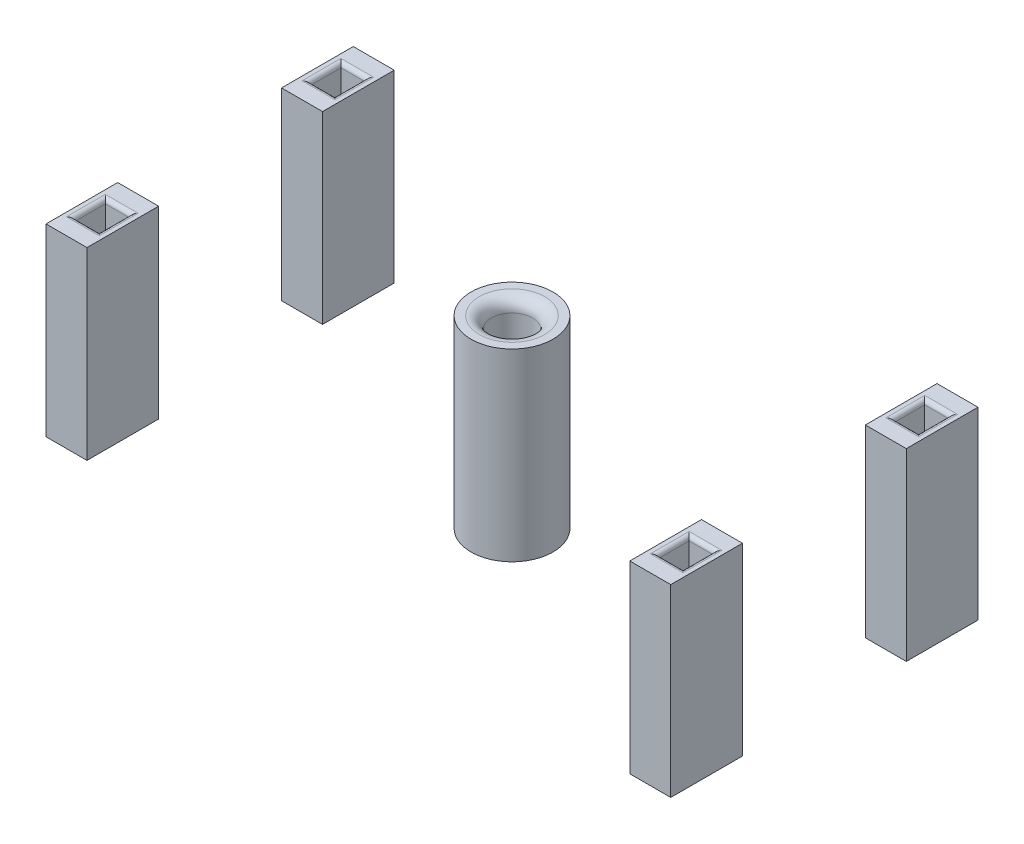
SolidWorks part; units mm, degrees
ref_plane "Front Plane" through (0, 0, 0) normal (0, 0, 1) x (1, 0, 0)
ref_plane "Top Plane" through (0, 0, 0) normal (0, 1, 0) x (1, 0, 0)
ref_plane "Right Plane" through (0, 0, 0) normal (1, 0, 0) x (0, 0, -1)
sketch "Sketch1" plane through (0, 0, 0) normal (0, 1, 0) x (1, 0, 0)
  line L0 (-55, 0) -> (55, 0) construction
  line L1 (-82.5, 43) -> (82.5, 43)
  line L2 (-82.5, 43) -> (-82.5, -43)
  line L3 (-82.5, -43) -> (82.5, -43)
  line L4 (82.5, 43) -> (82.5, -43)
  line L5 (-82.5, 43) -> (82.5, -43) construction
  line L6 (-82.5, -43) -> (82.5, 43) construction
  line L7 (-76.25, 37.5) -> (-66.25, 37.5)
  line L8 (-76.25, 37.5) -> (-76.25, -37.5)
  line L9 (-76.25, -37.5) -> (-66.25, -37.5)
  line L10 (-66.25, 37.5) -> (-66.25, -37.5)
  line L11 (-76.25, 37.5) -> (-66.25, -37.5) construction
  line L12 (-76.25, -37.5) -> (-66.25, 37.5) construction
  line L13 (-76.25, 20) -> (-66.25, 20)
  line L14 (-76.25, 20) -> (-76.25, -20)
  line L15 (-76.25, -20) -> (-66.25, -20)
  line L16 (-66.25, 20) -> (-66.25, -20)
  line L17 (-76.25, 20) -> (-66.25, -20) construction
  line L18 (-76.25, -20) -> (-66.25, 20) construction
  line L19 (-74.25, 32.5) -> (-68.25, 32.5)
  line L20 (-74.25, 32.5) -> (-74.25, 25)
  line L21 (-74.25, 25) -> (-68.25, 25)
  line L22 (-68.25, 32.5) -> (-68.25, 25)
  line L23 (-74.25, 32.5) -> (-68.25, 25) construction
  line L24 (-74.25, 25) -> (-68.25, 32.5) construction
  line L25 (-74.25, -25) -> (-68.25, -25)
  line L26 (-68.25, -32.5) -> (-68.25, -25)
  line L27 (-74.25, -32.5) -> (-68.25, -32.5)
  line L28 (-74.25, -32.5) -> (-74.25, -25)
  line L29 (0, -55) -> (0, 55) construction
  line L30 (76.25, -20) -> (66.25, -20)
  line L31 (66.25, 20) -> (66.25, -20)
  line L32 (76.25, 20) -> (66.25, 20)
  line L33 (76.25, 20) -> (76.25, -20)
  line L34 (74.25, -32.5) -> (74.25, -25)
  line L35 (74.25, -32.5) -> (68.25, -32.5)
  line L36 (68.25, -32.5) -> (68.25, -25)
  line L37 (74.25, -25) -> (68.25, -25)
  line L38 (74.25, 25) -> (68.25, 25)
  line L39 (68.25, 32.5) -> (68.25, 25)
  line L40 (74.25, 32.5) -> (68.25, 32.5)
  line L41 (74.25, 32.5) -> (74.25, 25)
  line L42 (76.25, -37.5) -> (66.25, -37.5)
  line L43 (66.25, 37.5) -> (66.25, -37.5)
  line L44 (76.25, 37.5) -> (66.25, 37.5)
  line L45 (76.25, 37.5) -> (76.25, -37.5)
  line L46 (76.25, -20) -> (66.25, -20)
  line L47 (66.25, 20) -> (66.25, -20)
  line L48 (76.25, 20) -> (66.25, 20)
  line L49 (76.25, 20) -> (76.25, -20)
  circle A0 centre (0, 0) radius 10
  circle A1 centre (0, 0) radius 5
  point P0 (0, 0)
  point P7 (-71.25, 0)
  point P13 (-82.5, 0)
  point P17 (-71.25, 0)
  point P23 (-71.25, 28.75)
  dimension "D3" = 20
  dimension "D4" = 10
  dimension "D1" = 165
  dimension "D2" = 86
  dimension "D5" = 5.5
  dimension "D6" = 6.25
  dimension "D7" = 10
  dimension "D8" = 40
  dimension "D9" = 5
  dimension "D10" = 5
  dimension "D11" = 2
  dimension "D12" = 2
extrude "Boss-Extrude1" add sketch "Sketch1" along normal blind 45 contours A0 A1 | L15 L8 L9 L10 L27 L28 L25 L26 | L8 L13 L10 L7 L19 L22 L21 L20 | L45 L44 L43 L32 L40 L41 L38 L39 | L45 L30 L43 L42 L37 L34 L35 L36
fillet "Fillet1" radius 1 8 edges at (-71.25, 0, -25) (-68.25, 0, -28.75) (-74.25, 0, -28.75) (-71.25, 0, -32.5) (-74.25, 45, -28.75) (-71.25, 45, -25) (-68.25, 45, -28.75) (-71.25, 45, -32.5)
fillet "Fillet2" radius 1 8 edges at (-74.25, 45, 28.75) (-71.25, 45, 25) (-71.25, 0, 25) (-74.25, 0, 28.75) (-68.25, 45, 28.75) (-68.25, 0, 28.75) (-71.25, 45, 32.5) (-71.25, 0, 32.5)
fillet "Fillet3" radius 1 8 edges at (68.25, 0, 28.75) (71.25, 0, 25) (74.25, 0, 28.75) (71.25, 0, 32.5) (71.25, 45, 32.5) (74.25, 45, 28.75) (68.25, 45, 28.75) (71.25, 45, 25)
fillet "Fillet4" radius 1 8 edges at (71.25, 0, -25) (74.25, 0, -28.75) (68.25, 0, -28.75) (71.25, 0, -32.5) (71.25, 45, -25) (74.25, 45, -28.75) (68.25, 45, -28.75) (71.25, 45, -32.5)
fillet "Fillet5" radius 3 2 edges at (0, 0, 5) (0, 45, 5)
